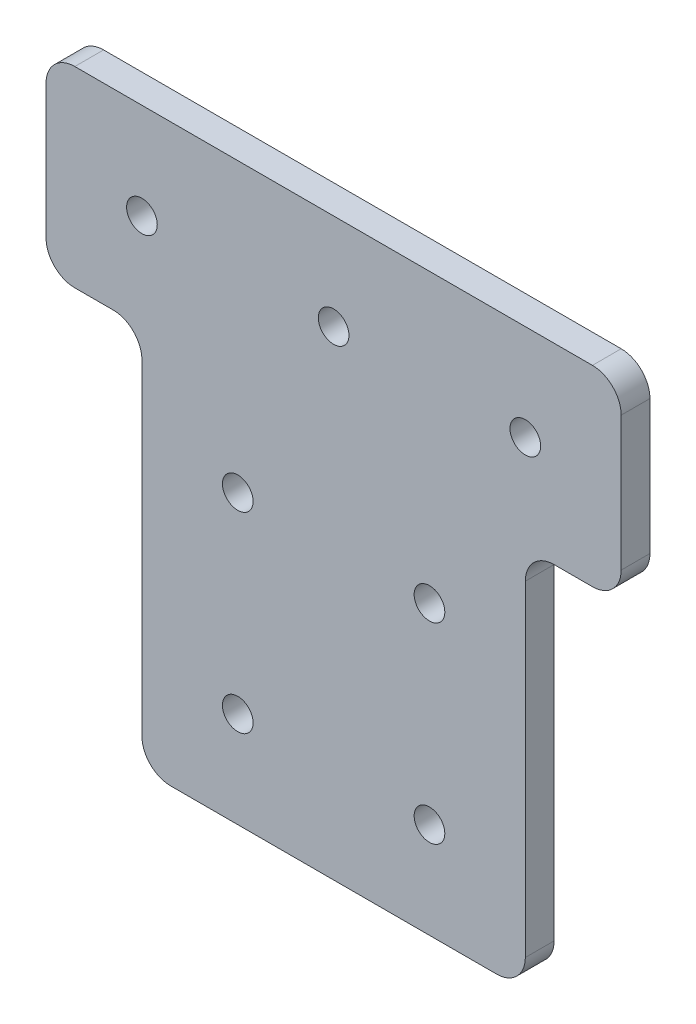
SolidWorks part; units mm, degrees
material "Thornel Mat VMA"
ref_plane "前视基准面" through (0, 0, 0) normal (0, 0, 1) x (1, 0, 0)
ref_plane "上视基准面" through (0, 0, 0) normal (0, 1, 0) x (1, 0, 0)
ref_plane "右视基准面" through (0, 0, 0) normal (1, 0, 0) x (0, 0, -1)
sketch "草图1" plane through (0, 0, 0) normal (0, 0, 1) x (1, 0, 0)
  line L0 (-20, 20) -> (-30, 20)
  line L6 (-20, 20) -> (-20, -20)
  line L11 (-20, -20) -> (20, -20)
  line L12 (20, 20) -> (20, -20)
  line L13 (-20, 20) -> (20, -20) construction
  line L14 (-20, -20) -> (20, 20) construction
  line L15 (30, 40) -> (-30, 40)
  line L16 (30, 40) -> (30, 20)
  line L17 (30, 20) -> (20, 20)
  line L18 (-30, 40) -> (-30, 20)
  point P0 (0, 0)
  dimension "D1" = 40
  dimension "D2" = 40
  dimension "D3" = 60
  dimension "D4" = 30
  dimension "D5" = 20
extrude "凸台-拉伸1" add sketch "草图1" along normal blind 3
sketch "草图2" plane through (0, 0, 3) normal (0, 0, 1) x (1, 0, 0)
  line L0 (-30, 40) -> (-30, 20) construction
  line L1 (30, 40) -> (-30, 40) construction
  line L2 (-20, 20) -> (-20, -20) construction
  line L3 (-20, -20) -> (20, -20) construction
  circle A0 centre (-20, 30) radius 1.6
  circle A1 centre (0, 30) radius 1.6
  circle A2 centre (20, 30) radius 1.6
  circle A3 centre (-10, -10) radius 1.6
  circle A4 centre (10, -10) radius 1.6
  circle A5 centre (10, 10) radius 1.6
  circle A6 centre (-10, 10) radius 1.6
  dimension "D1" = 3.2
  dimension "D7" = 3.2
  dimension "D2" = 10
  dimension "D3" = 10
  dimension "D5" = 10
  dimension "D6" = 10
  dimension "D4" = 3
  dimension "D8" = 2
  dimension "D9" = 2
extrude "切除-拉伸1" cut sketch "草图2" against normal up to next
fillet "圆角1" radius 3 6 edges at (20, -20, 1.5) (-20, -20, 1.5) (-30, 20, 1.5) (30, 20, 1.5) (30, 40, 1.5) (-30, 40, 1.5)
fillet "圆角2" radius 3 2 edges at (-20, 20, 1.5) (20, 20, 1.5)
